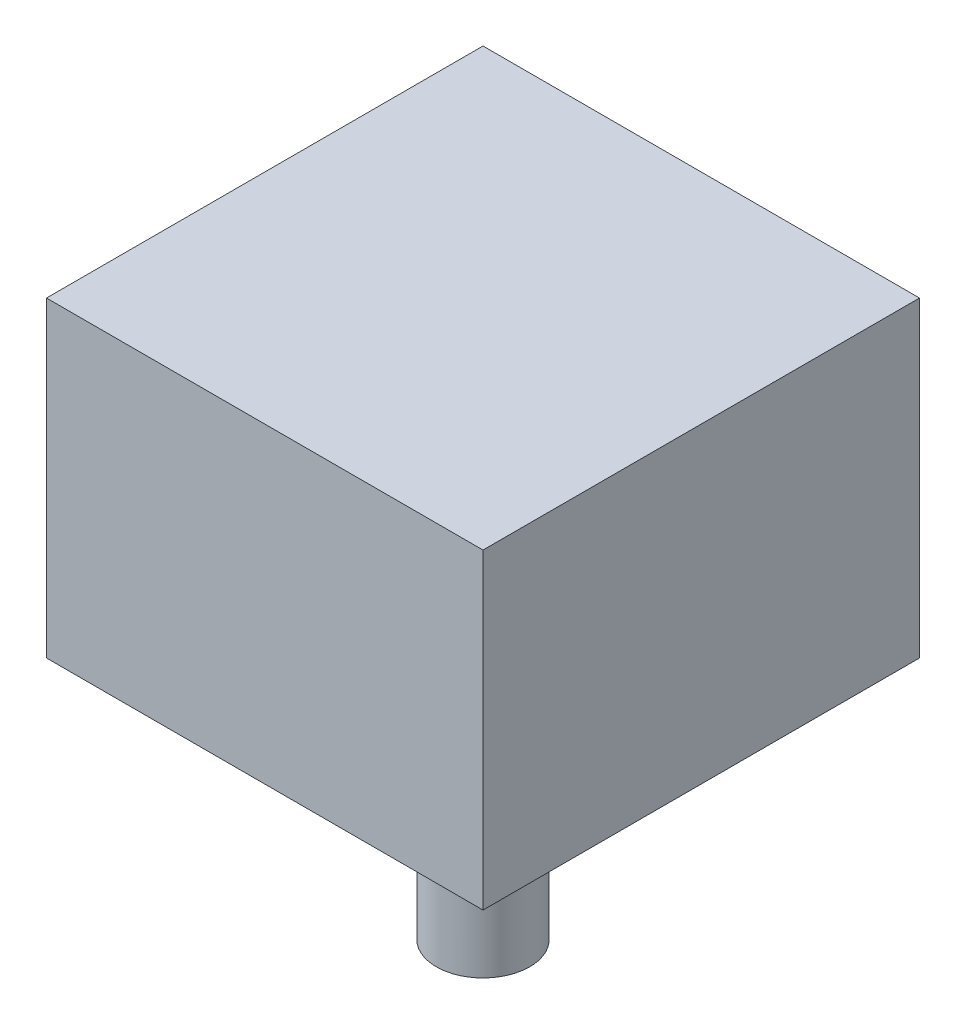
SolidWorks part; units mm, degrees
ref_plane "Front Plane" through (0, 0, 0) normal (0, 0, 1) x (1, 0, 0)
ref_plane "Top Plane" through (0, 0, 0) normal (0, 1, 0) x (1, 0, 0)
ref_plane "Right Plane" through (0, 0, 0) normal (1, 0, 0) x (0, 0, -1)
sketch "Sketch1" plane through (0, 0, 0) normal (0, 1, 0) x (1, 0, 0)
  line L1 (-14, 14) -> (14, 14)
  line L2 (-14, 14) -> (-14, -14)
  line L3 (-14, -14) -> (14, -14)
  line L4 (14, 14) -> (14, -14)
  line L5 (-14, 14) -> (14, -14) construction
  line L6 (-14, -14) -> (14, 14) construction
  point P0 (0, 0)
  dimension "D1" = 28
  dimension "D2" = 28
extrude "Boss-Extrude1" add sketch "Sketch1" against normal mid plane 20 contours L1 L4 L3 L2
sketch "Sketch2" plane through (0, 0, 0) normal (0, 0, 1) x (1, 0, 0)
  line L0 (0, -15) -> (0, -1)
  line L1 (0, -11) -> (0, 11) construction
  line L2 (-14, -10) -> (14, -10) construction
  arc A0 (0, -15) -> (0, -1) centre (0, -8) ccw
  dimension "D1" = 7
  dimension "D2" = 5
revolve "Cut-Revolve1" cut sketch "Sketch2" angle 360 about L0
sketch "Sketch3" plane through (0, 0, 0) normal (0, 0, 1) x (1, 0, 0)
  line L0 (0, -15) -> (0, -1) construction
  line L1 (0, -1.6) -> (0, -14.4)
  line L4 (0, -14.4) -> (0, -25.6533)
  line L5 (0, -25.6533) -> (3, -25.6533)
  line L6 (3, -13.6533) -> (3, -25.6533)
  arc A0 (3, -13.6533) -> (0, -1.6) centre (0, -8) ccw
  arc A1 (0, -15) -> (0, -1) centre (0, -8) ccw construction
  dimension "D1" = 0.6
  dimension "D2" = 3
  dimension "D3" = 12
revolve "Revolve1" add sketch "Sketch3" angle 360 about L0
sketch "Sketch4" plane through (0, 0, 14) normal (0, 0, 1) x (1, 0, 0)
  line L0 (3, -13.6533) -> (-3, -13.6533) construction
  circle A0 centre (0, -17.6533) radius 1.55
  point P4 (0, 0)
  dimension "D1" = 3.1
  dimension "D2" = 4
extrude "Cut-Extrude1" cut sketch "Sketch4" against normal through all both and the other way through all contours A0
